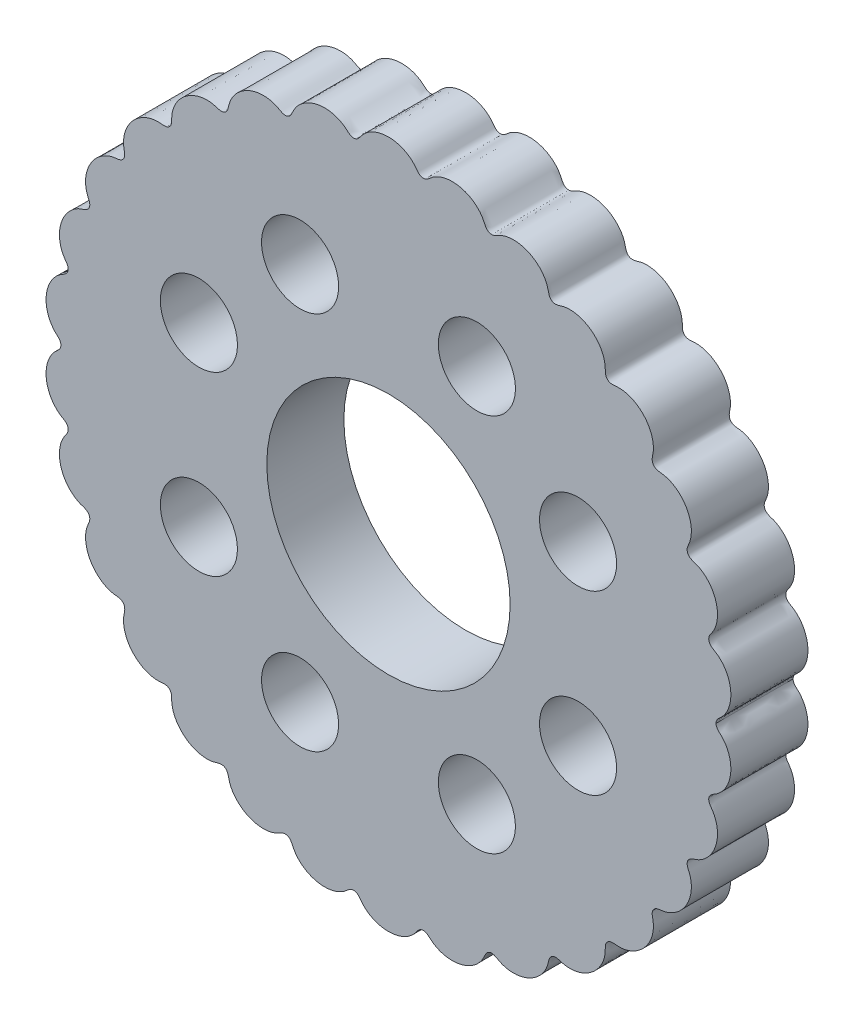
SolidWorks part; units mm, degrees
ref_plane "Plan de face" through (0, 0, 0) normal (0, 0, 1) x (1, 0, 0)
ref_plane "Plan de dessus" through (0, 0, 0) normal (0, 1, 0) x (1, 0, 0)
ref_plane "Plan de droite" through (0, 0, 0) normal (1, 0, 0) x (0, 0, -1)
sketch "Esquisse1" plane through (0, 0, 0) normal (0, 0, 1) x (1, 0, 0)
  line L0 (-1000, 0) -> (49000, 0) construction
  spline S0 degree 4 poles (29.8631, 8.2305) (29.8499, 8.1217) (29.8133, 7.9053) (29.7416, 7.64) (29.6157, 7.3353) (29.4839, 7.095) (29.3642, 6.911) (29.2467, 6.7537) (29.1538, 6.6056) (29.0902, 6.432) (29.0737, 6.2397) (29.1354, 6.023) (29.2904, 5.838) (29.4774, 5.7198) (29.6579, 5.6163) (29.8231, 5.5082) (30.0196, 5.3594) (30.2372, 5.1583) (30.5232, 4.8242) (30.8216, 4.3213) (31.0469, 3.679) (31.1337, 2.9091) (31.0567, 2.2277) (30.8902, 1.7108) (30.7109, 1.353) (30.5728, 1.1334) (30.4496, 0.9663) (30.3139, 0.8094) (30.1671, 0.6626) (30.0393, 0.549) (29.9425, 0.4546) (29.8803, 0.3777) (29.8449, 0.3262) (29.8141, 0.2716) (29.7888, 0.2141) (29.7717, 0.1632) (29.761, 0.1169) (29.7536, 0.0672) (29.7495, 0.017) (29.7494, -0.0206) (29.7556, -0.0898) (29.7678, -0.1499) (29.7904, -0.2203) (29.8284, -0.303) (29.8828, -0.3847) (29.9529, -0.4642) (30.04, -0.5488) (30.1416, -0.6407) (30.2572, -0.7512) (30.3813, -0.8854) (30.4962, -1.0277) (30.6276, -1.2147) (30.7721, -1.4641) (30.9126, -1.7829) (31.0276, -2.1744) (31.0935, -2.591) (31.107, -3.0187) (31.0662, -3.4508) (30.9693, -3.8803) (30.8145, -4.2991) (30.6117, -4.6792) (30.3965, -4.9766) (30.1917, -5.1998) (30.0146, -5.3603) (29.8643, -5.4786) (29.7061, -5.5858) (29.542, -5.684) (29.3671, -5.785) (29.2042, -5.9269) (29.0936, -6.1295) (29.0703, -6.371) (29.1391, -6.5914) (29.2598, -6.7697) (29.3791, -6.934) (29.4834, -7.0955) (29.5997, -7.3056) (29.715, -7.5703) (29.8147, -7.8969) (29.8798, -8.2857) (29.896, -8.684) (29.8631, -9.0858) (29.7829, -9.4799) (29.6574, -9.8612) (29.4885, -10.2243) (29.2783, -10.5643) (29.0303, -10.8742) (28.7824, -11.1148) (28.5506, -11.2952) (28.3468, -11.4258) (28.1768, -11.5188) (28.0006, -11.599) (27.8193, -11.6676) (27.6244, -11.7296) (27.4217, -11.8089) (27.242, -11.9571) (27.1301, -12.1734) (27.113, -12.404) (27.1707, -12.6114) (27.2542, -12.795) (27.3276, -12.9715) (27.3906, -13.1518) (27.4404, -13.3363) (27.4866, -13.5706) (27.5177, -13.8717) (27.5133, -14.2384) (27.4499, -14.6642) (27.3252, -15.0926) (27.1465, -15.4978) (26.919, -15.8739) (26.6474, -16.2153) (26.3365, -16.5168) (26.0024, -16.764) (25.654, -16.9563) (25.3418, -17.0779) (25.0791, -17.148) (24.8562, -17.1866) (24.6765, -17.2082) (24.4854, -17.2287) (24.2872, -17.2853) (24.1038, -17.4139) (23.9758, -17.6159) (23.9376, -17.8434) (23.9703, -18.0586) (24.0141, -18.2584) (24.0453, -18.4498) (24.0639, -18.6424) (24.0684, -18.8361) (24.0572, -19.0779) (24.0169, -19.3689) (23.9324, -19.7039) (23.7881, -20.0736) (23.5988, -20.4256) (23.3687, -20.7534) (23.1013, -21.0528) (22.8001, -21.3193) (22.4685, -21.5487) (22.1155, -21.7338) (21.7463, -21.8718) (21.4135, -21.9488) (21.1267, -21.9813) (20.8866, -21.9856) (20.6945, -21.9761) (20.4927, -21.9549) (20.2778, -21.9395) (20.0526, -21.9901) (19.8551, -22.131) (19.7349, -22.3281) (19.6935, -22.5401) (19.6935, -22.7421) (19.6905, -22.9333) (19.6768, -23.124) (19.6495, -23.3133) (19.599, -23.5469) (19.5081, -23.8358) (19.3582, -24.1709) (19.1304, -24.5365) (18.8451, -24.88) (18.5216, -25.1787) (18.1677, -25.4301) (17.7906, -25.6322) (17.3968, -25.7835) (17.0003, -25.8796) (16.6085, -25.9224) (16.2742, -25.9148) (16.002, -25.8785) (15.7793, -25.8278) (15.6036, -25.7769) (15.4169, -25.7147) (15.2087, -25.6689) (14.9779, -25.6954) (14.7639, -25.8189) (14.6256, -26.0056) (14.5611, -26.2088) (14.5217, -26.4015) (14.4779, -26.5791) (14.4104, -26.7974) (14.3058, -27.0513) (14.1452, -27.3445) (13.9122, -27.6625) (13.6308, -27.9579) (13.3029, -28.2232) (12.9393, -28.4488) (12.5446, -28.6295) (12.1242, -28.7604) (11.6841, -28.8357) (11.2535, -28.8501) (10.8884, -28.8124) (10.5927, -28.7466) (10.3651, -28.6736) (10.1875, -28.6026) (10.0156, -28.5191) (9.8485, -28.4261) (9.6736, -28.3252) (9.4693, -28.255) (9.2385, -28.2605) (9.0177, -28.3611) (8.8612, -28.5309) (8.7671, -28.7246) (8.6846, -28.91) (8.5968, -29.0812) (8.473, -29.2869) (8.3014, -29.519) (8.0684, -29.7687) (7.7643, -30.0195) (7.4274, -30.2327) (7.0631, -30.4051) (6.6816, -30.5327) (6.2887, -30.6146) (5.8897, -30.6499) (5.4902, -30.6379) (5.0979, -30.5781) (4.7655, -30.4837) (4.4934, -30.3731) (4.2784, -30.2619) (4.1128, -30.1612) (3.9553, -30.0487) (3.8052, -29.926) (3.6541, -29.7882) (3.484, -29.6523) (3.2679, -29.5716) (3.029, -29.5815) (2.8259, -29.676) (2.6778, -29.8193) (2.5645, -29.9746) (2.456, -30.1194) (2.311, -30.2931) (2.119, -30.4856) (1.8576, -30.6952) (1.5168, -30.9007) (1.1357, -31.0665) (0.7192, -31.185) (0.2877, -31.2495) (-0.1517, -31.2585) (-0.592, -31.2106) (-1.0254, -31.1045) (-1.4258, -30.9464) (-1.7456, -30.7669) (-1.9908, -30.5894) (-2.1706, -30.4322) (-2.3055, -30.2968) (-2.4301, -30.1521) (-2.5463, -30.0003) (-2.6635, -29.8363) (-2.8143, -29.6826) (-3.0226, -29.582) (-3.2659, -29.5708) (-3.484, -29.6523) (-3.654, -29.7882) (-3.8052, -29.926) (-3.9553, -30.0487) (-4.1128, -30.1612) (-4.2784, -30.2619) (-4.4934, -30.3731) (-4.7655, -30.4837) (-5.0979, -30.5781) (-5.4902, -30.6379) (-5.8897, -30.6499) (-6.2887, -30.6146) (-6.6816, -30.5327) (-7.0631, -30.4051) (-7.4274, -30.2327) (-7.7643, -30.0195) (-8.0684, -29.7687) (-8.3014, -29.519) (-8.473, -29.2869) (-8.5968, -29.0812) (-8.6846, -28.91) (-8.7671, -28.7246) (-8.8612, -28.5309) (-9.0177, -28.3611) (-9.2385, -28.2605) (-9.4693, -28.255) (-9.6736, -28.3252) (-9.8485, -28.4261) (-10.0156, -28.5191) (-10.1875, -28.6026) (-10.3651, -28.6736) (-10.5927, -28.7466) (-10.8884, -28.8124) (-11.2535, -28.8501) (-11.6841, -28.8357) (-12.1242, -28.7604) (-12.5446, -28.6295) (-12.9393, -28.4488) (-13.3029, -28.2232) (-13.6308, -27.9579) (-13.9122, -27.6625) (-14.1452, -27.3445) (-14.3058, -27.0513) (-14.4104, -26.7974) (-14.4779, -26.5791) (-14.5217, -26.4015) (-14.5611, -26.2088) (-14.6256, -26.0056) (-14.7639, -25.8189) (-14.9779, -25.6954) (-15.2087, -25.6689) (-15.4169, -25.7147) (-15.6036, -25.7769) (-15.7793, -25.8278) (-16.002, -25.8785) (-16.2742, -25.9148) (-16.6085, -25.9224) (-17.0003, -25.8796) (-17.3968, -25.7835) (-17.7906, -25.6322) (-18.1677, -25.4301) (-18.5216, -25.1787) (-18.8451, -24.88) (-19.1304, -24.5365) (-19.3582, -24.1709) (-19.5081, -23.8358) (-19.599, -23.5469) (-19.6495, -23.3133) (-19.6768, -23.124) (-19.6905, -22.9333) (-19.6935, -22.7421) (-19.6935, -22.5401) (-19.7349, -22.3281) (-19.8551, -22.131) (-20.0526, -21.9901) (-20.2778, -21.9395) (-20.4927, -21.9549) (-20.6945, -21.9761) (-20.8866, -21.9856) (-21.1267, -21.9813) (-21.4135, -21.9488) (-21.7463, -21.8718) (-22.1155, -21.7338) (-22.4685, -21.5487) (-22.8001, -21.3193) (-23.1013, -21.0528) (-23.3687, -20.7534) (-23.5988, -20.4256) (-23.7881, -20.0736) (-23.9324, -19.7039) (-24.0169, -19.3689) (-24.0572, -19.0779) (-24.0684, -18.8361) (-24.0639, -18.6424) (-24.0453, -18.4498) (-24.0141, -18.2584) (-23.9703, -18.0586) (-23.9376, -17.8434) (-23.9758, -17.6159) (-24.1038, -17.4139) (-24.2872, -17.2853) (-24.4854, -17.2287) (-24.6765, -17.2082) (-24.8562, -17.1866) (-25.0791, -17.148) (-25.3418, -17.0779) (-25.654, -16.9563) (-26.0024, -16.764) (-26.3365, -16.5168) (-26.6474, -16.2153) (-26.919, -15.8739) (-27.1465, -15.4978) (-27.3252, -15.0926) (-27.4499, -14.6642) (-27.5133, -14.2384) (-27.5177, -13.8717) (-27.4866, -13.5706) (-27.4404, -13.3363) (-27.3906, -13.1518) (-27.3276, -12.9715) (-27.2542, -12.795) (-27.1707, -12.6114) (-27.113, -12.404) (-27.1301, -12.1734) (-27.242, -11.9571) (-27.4217, -11.8089) (-27.6244, -11.7296) (-27.8193, -11.6676) (-28.0006, -11.599) (-28.1768, -11.5188) (-28.3468, -11.4258) (-28.5506, -11.2952) (-28.7824, -11.1148) (-29.0303, -10.8742) (-29.2783, -10.5643) (-29.4885, -10.2243) (-29.6574, -9.8612) (-29.7829, -9.4799) (-29.8631, -9.0858) (-29.896, -8.684) (-29.8798, -8.2857) (-29.8147, -7.8969) (-29.715, -7.5703) (-29.5997, -7.3056) (-29.4834, -7.0955) (-29.3791, -6.934) (-29.2598, -6.7697) (-29.1391, -6.5914) (-29.0703, -6.371) (-29.0936, -6.1295) (-29.2042, -5.9269) (-29.3671, -5.785) (-29.542, -5.684) (-29.7061, -5.5858) (-29.8643, -5.4786) (-30.0146, -5.3603) (-30.1917, -5.1998) (-30.3965, -4.9766) (-30.6117, -4.6792) (-30.8145, -4.2991) (-30.9693, -3.8803) (-31.0662, -3.4508) (-31.107, -3.0187) (-31.0935, -2.591) (-31.0276, -2.1744) (-30.9126, -1.7829) (-30.7537, -1.4222) (-30.58, -1.1364) (-30.4124, -0.919) (-30.2572, -0.7512) (-30.1416, -0.6407) (-30.04, -0.5488) (-29.9529, -0.4642) (-29.8828, -0.3847) (-29.8284, -0.303) (-29.7904, -0.2203) (-29.7678, -0.1499) (-29.7556, -0.0898) (-29.7494, -0.0206) (-29.7495, 0.0226) (-29.7561, 0.094) (-29.7693, 0.1557) (-29.7888, 0.2141) (-29.8141, 0.2716) (-29.8449, 0.3262) (-29.8803, 0.3778) (-29.9262, 0.4344) (-29.9834, 0.4947) (-30.0703, 0.5765) (-30.1854, 0.6811) (-30.3139, 0.8093) (-30.4835, 1.0056) (-30.6621, 1.2611) (-30.8291, 1.576) (-30.9678, 1.9517) (-31.0574, 2.3341) (-31.1011, 2.7166) (-31.1012, 3.1978) (-31.0148, 3.7704) (-30.8216, 4.3213) (-30.5232, 4.8242) (-30.2372, 5.1583) (-30.0196, 5.3594) (-29.8231, 5.5082) (-29.6579, 5.6163) (-29.4774, 5.7198) (-29.2904, 5.838) (-29.1354, 6.023) (-29.0737, 6.2397) (-29.0902, 6.432) (-29.1538, 6.6056) (-29.2467, 6.7537) (-29.3642, 6.911) (-29.4839, 7.095) (-29.6157, 7.3353) (-29.7416, 7.64) (-29.8133, 7.9053) (-29.8499, 8.1217) (-29.8631, 8.2305) knots 0 0 0 0 0 0.003392 0.006784 0.00848 0.010176 0.011872 0.013568 0.014566 0.015563 0.017559 0.01944 0.02132 0.022846 0.024371 0.025896 0.027421 0.030471 0.033522 0.039468 0.045414 0.051361 0.057307 0.060517 0.062121 0.063726 0.065331 0.066935 0.06854 0.070145 0.070628 0.071112 0.071596 0.07208 0.072564 0.073048 0.073289 0.073531 0.074015 0.07448 0.074945 0.07541 0.075875 0.076805 0.077735 0.078442 0.079149 0.080563 0.081977 0.083391 0.084805 0.086218 0.089046 0.092302 0.095557 0.098813 0.102069 0.105514 0.10896 0.112405 0.115851 0.118808 0.120287 0.121766 0.123244 0.124723 0.126202 0.12768 0.1295 0.131319 0.133154 0.134989 0.136475 0.137961 0.139448 0.140934 0.143906 0.146878 0.14999 0.153103 0.156215 0.159327 0.162414 0.1655 0.168586 0.171672 0.174668 0.176165 0.177663 0.179161 0.180659 0.182156 0.183654 0.185506 0.187357 0.189175 0.190994 0.192471 0.193949 0.195426 0.196904 0.198382 0.199859 0.202814 0.206257 0.2097 0.213143 0.216586 0.219928 0.22327 0.226613 0.229955 0.232755 0.235555 0.236955 0.238355 0.239755 0.241155 0.242909 0.244663 0.246515 0.248366 0.249864 0.251362 0.252859 0.254357 0.255855 0.257353 0.260348 0.263434 0.266521 0.269607 0.272693 0.275805 0.278918 0.28203 0.285143 0.288115 0.291087 0.292573 0.294059 0.295545 0.297031 0.298866 0.300701 0.302521 0.30434 0.305819 0.307297 0.308776 0.310255 0.311733 0.313212 0.31617 0.319615 0.323061 0.326506 0.329952 0.333207 0.336463 0.339719 0.342974 0.345802 0.34863 0.350043 0.351457 0.352871 0.354285 0.356145 0.358005 0.359865 0.361725 0.363139 0.364553 0.365967 0.367381 0.370208 0.373036 0.376292 0.379547 0.382803 0.386059 0.389504 0.39295 0.396395 0.399841 0.402798 0.404277 0.405755 0.407234 0.408713 0.410191 0.41167 0.41349 0.415309 0.417144 0.418979 0.420465 0.421951 0.423437 0.424923 0.427896 0.430868 0.43398 0.437092 0.440205 0.443317 0.446403 0.44949 0.452576 0.455662 0.458657 0.460155 0.461653 0.463151 0.464649 0.466146 0.467644 0.469495 0.471347 0.473101 0.474856 0.476256 0.477656 0.479056 0.480456 0.483256 0.486055 0.489398 0.49274 0.496082 0.499424 0.502867 0.50631 0.509753 0.513196 0.516151 0.517629 0.519106 0.520584 0.522061 0.523539 0.525016 0.526835 0.528653 0.530505 0.532356 0.533854 0.535351 0.536849 0.538347 0.539845 0.541343 0.544338 0.547424 0.55051 0.553597 0.556683 0.559795 0.562908 0.56602 0.569132 0.572104 0.575077 0.576563 0.578049 0.579535 0.581021 0.582856 0.584691 0.58651 0.58833 0.589809 0.591287 0.592766 0.594245 0.595723 0.597202 0.600159 0.603605 0.60705 0.610496 0.613941 0.617197 0.620453 0.623708 0.626964 0.629792 0.632619 0.634033 0.635447 0.636861 0.638275 0.640135 0.641995 0.643855 0.645715 0.647129 0.648543 0.649957 0.65137 0.654198 0.657026 0.660281 0.663537 0.666793 0.670048 0.673494 0.676939 0.680385 0.68383 0.686788 0.688267 0.689745 0.691224 0.692703 0.694181 0.69566 0.697479 0.699299 0.701134 0.702969 0.704455 0.705941 0.707427 0.708913 0.711885 0.714857 0.71797 0.721082 0.724195 0.727307 0.730393 0.733479 0.736566 0.739652 0.742647 0.744145 0.745643 0.747141 0.748638 0.750136 0.751634 0.753485 0.755337 0.757091 0.758845 0.760245 0.761645 0.763045 0.764445 0.767245 0.770045 0.773387 0.77673 0.780072 0.783414 0.786857 0.7903 0.793743 0.797186 0.800141 0.801618 0.803096 0.804574 0.806051 0.807529 0.809006 0.810825 0.812643 0.814494 0.816346 0.817844 0.819341 0.820839 0.822337 0.823835 0.825332 0.828328 0.831414 0.8345 0.837586 0.840673 0.843785 0.846897 0.85001 0.853122 0.856094 0.859066 0.860552 0.862039 0.863525 0.865011 0.866846 0.868681 0.8705 0.87232 0.873798 0.875277 0.876756 0.878234 0.879713 0.881192 0.884149 0.887595 0.89104 0.894486 0.897931 0.901187 0.904443 0.907698 0.910954 0.913782 0.916609 0.918023 0.919437 0.920851 0.921558 0.922265 0.923195 0.924125 0.92459 0.925055 0.92552 0.925985 0.926469 0.926952 0.927436 0.92792 0.928404 0.928888 0.929372 0.929855 0.930658 0.93146 0.933065 0.934669 0.936274 0.939483 0.942693 0.945666 0.948639 0.951612 0.954586 0.960532 0.966478 0.969529 0.972579 0.974104 0.975629 0.977154 0.97868 0.98056 0.982441 0.984437 0.985434 0.986432 0.988128 0.989824 0.99152 0.993216 0.996608 1 1 1 1 1 construction
  spline S1 degree 4 poles (29.75, 0) (29.75, -0.0128) (29.751, -0.0384) (29.7556, -0.0898) (29.7678, -0.1499) (29.7904, -0.2203) (29.8284, -0.303) (29.8828, -0.3847) (29.9529, -0.4642) (30.04, -0.5488) (30.1416, -0.6407) (30.2572, -0.7512) (30.3813, -0.8854) (30.4962, -1.0277) (30.6276, -1.2147) (30.7721, -1.4641) (30.9126, -1.7829) (31.0276, -2.1744) (31.0935, -2.591) (31.107, -3.0187) (31.0662, -3.4508) (30.9693, -3.8803) (30.8145, -4.2991) (30.6117, -4.6792) (30.3965, -4.9766) (30.1917, -5.1998) (30.0146, -5.3603) (29.8643, -5.4786) (29.7061, -5.5858) (29.542, -5.684) (29.3671, -5.785) (29.2042, -5.9269) (29.0936, -6.1295) (29.0703, -6.371) (29.1391, -6.5914) (29.2598, -6.7697) (29.3791, -6.934) (29.4834, -7.0955) (29.5997, -7.3056) (29.715, -7.5703) (29.8147, -7.8969) (29.8798, -8.2857) (29.896, -8.684) (29.8631, -9.0858) (29.7829, -9.4799) (29.6574, -9.8612) (29.4885, -10.2243) (29.2783, -10.5643) (29.0303, -10.8742) (28.7824, -11.1148) (28.5506, -11.2952) (28.3468, -11.4258) (28.1768, -11.5188) (28.0006, -11.599) (27.8193, -11.6676) (27.6244, -11.7296) (27.4217, -11.8089) (27.242, -11.9571) (27.1301, -12.1734) (27.113, -12.404) (27.1707, -12.6114) (27.2542, -12.795) (27.3276, -12.9715) (27.3906, -13.1518) (27.4404, -13.3363) (27.4866, -13.5706) (27.5177, -13.8717) (27.5133, -14.2384) (27.4499, -14.6642) (27.3252, -15.0926) (27.1465, -15.4978) (26.919, -15.8739) (26.6474, -16.2153) (26.3365, -16.5168) (26.0024, -16.764) (25.654, -16.9563) (25.3418, -17.0779) (25.0791, -17.148) (24.8562, -17.1866) (24.6765, -17.2082) (24.4854, -17.2287) (24.2872, -17.2853) (24.1038, -17.4139) (23.9758, -17.6159) (23.9376, -17.8434) (23.9703, -18.0586) (24.0141, -18.2584) (24.0453, -18.4498) (24.0639, -18.6424) (24.0684, -18.8361) (24.0572, -19.0779) (24.0169, -19.3689) (23.9324, -19.7039) (23.7881, -20.0736) (23.5988, -20.4256) (23.3687, -20.7534) (23.1013, -21.0528) (22.8001, -21.3193) (22.4685, -21.5487) (22.1155, -21.7338) (21.7463, -21.8718) (21.4135, -21.9488) (21.1267, -21.9813) (20.8866, -21.9856) (20.6945, -21.9761) (20.4927, -21.9549) (20.2778, -21.9395) (20.0526, -21.9901) (19.8551, -22.131) (19.7349, -22.3281) (19.6935, -22.5401) (19.6935, -22.7421) (19.6905, -22.9333) (19.6768, -23.124) (19.6495, -23.3133) (19.599, -23.5469) (19.5081, -23.8358) (19.3582, -24.1709) (19.1304, -24.5365) (18.8451, -24.88) (18.5216, -25.1787) (18.1677, -25.4301) (17.7906, -25.6322) (17.3968, -25.7835) (17.0003, -25.8796) (16.6085, -25.9224) (16.2742, -25.9148) (16.002, -25.8785) (15.7793, -25.8278) (15.6036, -25.7769) (15.4169, -25.7147) (15.2087, -25.6689) (14.9779, -25.6954) (14.7639, -25.8189) (14.6256, -26.0056) (14.5611, -26.2088) (14.5217, -26.4015) (14.4779, -26.5791) (14.4104, -26.7974) (14.3058, -27.0513) (14.1452, -27.3445) (13.9122, -27.6625) (13.6308, -27.9579) (13.3029, -28.2232) (12.9393, -28.4488) (12.5446, -28.6295) (12.1242, -28.7604) (11.6841, -28.8357) (11.2535, -28.8501) (10.8884, -28.8124) (10.5927, -28.7466) (10.3651, -28.6736) (10.1875, -28.6026) (10.0156, -28.5191) (9.8485, -28.4261) (9.6736, -28.3252) (9.4693, -28.255) (9.2385, -28.2605) (9.0177, -28.3611) (8.8612, -28.5309) (8.7671, -28.7246) (8.6846, -28.91) (8.5968, -29.0812) (8.473, -29.2869) (8.3014, -29.519) (8.0684, -29.7687) (7.7643, -30.0195) (7.4274, -30.2327) (7.0631, -30.4051) (6.6816, -30.5327) (6.2887, -30.6146) (5.8897, -30.6499) (5.4902, -30.6379) (5.0979, -30.5781) (4.7655, -30.4837) (4.4934, -30.3731) (4.2784, -30.2619) (4.1128, -30.1612) (3.9553, -30.0487) (3.8052, -29.926) (3.6541, -29.7882) (3.484, -29.6523) (3.2679, -29.5716) (3.029, -29.5815) (2.8259, -29.676) (2.6778, -29.8193) (2.5645, -29.9746) (2.456, -30.1194) (2.311, -30.2931) (2.119, -30.4856) (1.8576, -30.6952) (1.5168, -30.9007) (1.1357, -31.0665) (0.7192, -31.185) (0.2877, -31.2495) (-0.1517, -31.2585) (-0.592, -31.2106) (-1.0254, -31.1045) (-1.4258, -30.9464) (-1.7456, -30.7669) (-1.9908, -30.5894) (-2.1706, -30.4322) (-2.3055, -30.2968) (-2.4301, -30.1521) (-2.5463, -30.0003) (-2.6635, -29.8363) (-2.8143, -29.6826) (-3.0226, -29.582) (-3.2659, -29.5708) (-3.484, -29.6523) (-3.654, -29.7882) (-3.8052, -29.926) (-3.9553, -30.0487) (-4.1128, -30.1612) (-4.2784, -30.2619) (-4.4934, -30.3731) (-4.7655, -30.4837) (-5.0979, -30.5781) (-5.4902, -30.6379) (-5.8897, -30.6499) (-6.2887, -30.6146) (-6.6816, -30.5327) (-7.0631, -30.4051) (-7.4274, -30.2327) (-7.7643, -30.0195) (-8.0684, -29.7687) (-8.3014, -29.519) (-8.473, -29.2869) (-8.5968, -29.0812) (-8.6846, -28.91) (-8.7671, -28.7246) (-8.8612, -28.5309) (-9.0177, -28.3611) (-9.2385, -28.2605) (-9.4693, -28.255) (-9.6736, -28.3252) (-9.8485, -28.4261) (-10.0156, -28.5191) (-10.1875, -28.6026) (-10.3651, -28.6736) (-10.5927, -28.7466) (-10.8884, -28.8124) (-11.2535, -28.8501) (-11.6841, -28.8357) (-12.1242, -28.7604) (-12.5446, -28.6295) (-12.9393, -28.4488) (-13.3029, -28.2232) (-13.6308, -27.9579) (-13.9122, -27.6625) (-14.1452, -27.3445) (-14.3058, -27.0513) (-14.4104, -26.7974) (-14.4779, -26.5791) (-14.5217, -26.4015) (-14.5611, -26.2088) (-14.6256, -26.0056) (-14.7639, -25.8189) (-14.9779, -25.6954) (-15.2087, -25.6689) (-15.4169, -25.7147) (-15.6036, -25.7769) (-15.7793, -25.8278) (-16.002, -25.8785) (-16.2742, -25.9148) (-16.6085, -25.9224) (-17.0003, -25.8796) (-17.3968, -25.7835) (-17.7906, -25.6322) (-18.1677, -25.4301) (-18.5216, -25.1787) (-18.8451, -24.88) (-19.1304, -24.5365) (-19.3582, -24.1709) (-19.5081, -23.8358) (-19.599, -23.5469) (-19.6495, -23.3133) (-19.6768, -23.124) (-19.6905, -22.9333) (-19.6935, -22.7421) (-19.6935, -22.5401) (-19.7349, -22.3281) (-19.8551, -22.131) (-20.0526, -21.9901) (-20.2778, -21.9395) (-20.4927, -21.9549) (-20.6945, -21.9761) (-20.8866, -21.9856) (-21.1267, -21.9813) (-21.4135, -21.9488) (-21.7463, -21.8718) (-22.1155, -21.7338) (-22.4685, -21.5487) (-22.8001, -21.3193) (-23.1013, -21.0528) (-23.3687, -20.7534) (-23.5988, -20.4256) (-23.7881, -20.0736) (-23.9324, -19.7039) (-24.0169, -19.3689) (-24.0572, -19.0779) (-24.0684, -18.8361) (-24.0639, -18.6424) (-24.0453, -18.4498) (-24.0141, -18.2584) (-23.9703, -18.0586) (-23.9376, -17.8434) (-23.9758, -17.6159) (-24.1038, -17.4139) (-24.2872, -17.2853) (-24.4854, -17.2287) (-24.6765, -17.2082) (-24.8562, -17.1866) (-25.0791, -17.148) (-25.3418, -17.0779) (-25.654, -16.9563) (-26.0024, -16.764) (-26.3365, -16.5168) (-26.6474, -16.2153) (-26.919, -15.8739) (-27.1465, -15.4978) (-27.3252, -15.0926) (-27.4499, -14.6642) (-27.5133, -14.2384) (-27.5177, -13.8717) (-27.4866, -13.5706) (-27.4404, -13.3363) (-27.3906, -13.1518) (-27.3276, -12.9715) (-27.2542, -12.795) (-27.1707, -12.6114) (-27.113, -12.404) (-27.1301, -12.1734) (-27.242, -11.9571) (-27.4217, -11.8089) (-27.6244, -11.7296) (-27.8193, -11.6676) (-28.0006, -11.599) (-28.1768, -11.5188) (-28.3468, -11.4258) (-28.5506, -11.2952) (-28.7824, -11.1148) (-29.0303, -10.8742) (-29.2783, -10.5643) (-29.4885, -10.2243) (-29.6574, -9.8612) (-29.7829, -9.4799) (-29.8631, -9.0858) (-29.896, -8.684) (-29.8798, -8.2857) (-29.8147, -7.8969) (-29.715, -7.5703) (-29.5997, -7.3056) (-29.4834, -7.0955) (-29.3791, -6.934) (-29.2598, -6.7697) (-29.1391, -6.5914) (-29.0703, -6.371) (-29.0936, -6.1295) (-29.2042, -5.9269) (-29.3671, -5.785) (-29.542, -5.684) (-29.7061, -5.5858) (-29.8643, -5.4786) (-30.0146, -5.3603) (-30.1917, -5.1998) (-30.3965, -4.9766) (-30.6117, -4.6792) (-30.8145, -4.2991) (-30.9693, -3.8803) (-31.0662, -3.4508) (-31.107, -3.0187) (-31.0935, -2.591) (-31.0276, -2.1744) (-30.9126, -1.7829) (-30.7537, -1.4222) (-30.58, -1.1364) (-30.4124, -0.919) (-30.2572, -0.7512) (-30.1416, -0.6407) (-30.04, -0.5488) (-29.9529, -0.4642) (-29.8828, -0.3847) (-29.8284, -0.303) (-29.7904, -0.2203) (-29.7678, -0.1499) (-29.7556, -0.0898) (-29.751, -0.0384) (-29.75, -0.0128) (-29.75, 0) knots 0.074015 0.074015 0.074015 0.074015 0.074015 0.07448 0.074945 0.07541 0.075875 0.076805 0.077735 0.078442 0.079149 0.080563 0.081977 0.083391 0.084805 0.086218 0.089046 0.092302 0.095557 0.098813 0.102069 0.105514 0.10896 0.112405 0.115851 0.118808 0.120287 0.121766 0.123244 0.124723 0.126202 0.12768 0.1295 0.131319 0.133154 0.134989 0.136475 0.137961 0.139448 0.140934 0.143906 0.146878 0.14999 0.153103 0.156215 0.159327 0.162414 0.1655 0.168586 0.171672 0.174668 0.176165 0.177663 0.179161 0.180659 0.182156 0.183654 0.185506 0.187357 0.189175 0.190994 0.192471 0.193949 0.195426 0.196904 0.198382 0.199859 0.202814 0.206257 0.2097 0.213143 0.216586 0.219928 0.22327 0.226613 0.229955 0.232755 0.235555 0.236955 0.238355 0.239755 0.241155 0.242909 0.244663 0.246515 0.248366 0.249864 0.251362 0.252859 0.254357 0.255855 0.257353 0.260348 0.263434 0.266521 0.269607 0.272693 0.275805 0.278918 0.28203 0.285143 0.288115 0.291087 0.292573 0.294059 0.295545 0.297031 0.298866 0.300701 0.302521 0.30434 0.305819 0.307297 0.308776 0.310255 0.311733 0.313212 0.31617 0.319615 0.323061 0.326506 0.329952 0.333207 0.336463 0.339719 0.342974 0.345802 0.34863 0.350043 0.351457 0.352871 0.354285 0.356145 0.358005 0.359865 0.361725 0.363139 0.364553 0.365967 0.367381 0.370208 0.373036 0.376292 0.379547 0.382803 0.386059 0.389504 0.39295 0.396395 0.399841 0.402798 0.404277 0.405755 0.407234 0.408713 0.410191 0.41167 0.41349 0.415309 0.417144 0.418979 0.420465 0.421951 0.423437 0.424923 0.427896 0.430868 0.43398 0.437092 0.440205 0.443317 0.446403 0.44949 0.452576 0.455662 0.458657 0.460155 0.461653 0.463151 0.464649 0.466146 0.467644 0.469495 0.471347 0.473101 0.474856 0.476256 0.477656 0.479056 0.480456 0.483256 0.486055 0.489398 0.49274 0.496082 0.499424 0.502867 0.50631 0.509753 0.513196 0.516151 0.517629 0.519106 0.520584 0.522061 0.523539 0.525016 0.526835 0.528653 0.530505 0.532356 0.533854 0.535351 0.536849 0.538347 0.539845 0.541343 0.544338 0.547424 0.55051 0.553597 0.556683 0.559795 0.562908 0.56602 0.569132 0.572104 0.575077 0.576563 0.578049 0.579535 0.581021 0.582856 0.584691 0.58651 0.58833 0.589809 0.591287 0.592766 0.594245 0.595723 0.597202 0.600159 0.603605 0.60705 0.610496 0.613941 0.617197 0.620453 0.623708 0.626964 0.629792 0.632619 0.634033 0.635447 0.636861 0.638275 0.640135 0.641995 0.643855 0.645715 0.647129 0.648543 0.649957 0.65137 0.654198 0.657026 0.660281 0.663537 0.666793 0.670048 0.673494 0.676939 0.680385 0.68383 0.686788 0.688267 0.689745 0.691224 0.692703 0.694181 0.69566 0.697479 0.699299 0.701134 0.702969 0.704455 0.705941 0.707427 0.708913 0.711885 0.714857 0.71797 0.721082 0.724195 0.727307 0.730393 0.733479 0.736566 0.739652 0.742647 0.744145 0.745643 0.747141 0.748638 0.750136 0.751634 0.753485 0.755337 0.757091 0.758845 0.760245 0.761645 0.763045 0.764445 0.767245 0.770045 0.773387 0.77673 0.780072 0.783414 0.786857 0.7903 0.793743 0.797186 0.800141 0.801618 0.803096 0.804574 0.806051 0.807529 0.809006 0.810825 0.812643 0.814494 0.816346 0.817844 0.819341 0.820839 0.822337 0.823835 0.825332 0.828328 0.831414 0.8345 0.837586 0.840673 0.843785 0.846897 0.85001 0.853122 0.856094 0.859066 0.860552 0.862039 0.863525 0.865011 0.866846 0.868681 0.8705 0.87232 0.873798 0.875277 0.876756 0.878234 0.879713 0.881192 0.884149 0.887595 0.89104 0.894486 0.897931 0.901187 0.904443 0.907698 0.910954 0.913782 0.916609 0.918023 0.919437 0.920851 0.921558 0.922265 0.923195 0.924125 0.92459 0.925055 0.92552 0.925985 0.925985 0.925985 0.925985 0.925985 construction
  spline S2 degree 4 poles (29.75, 0) (29.75, 0.0128) (29.751, 0.0384) (29.7556, 0.0898) (29.7678, 0.1499) (29.7904, 0.2203) (29.8284, 0.303) (29.8828, 0.3847) (29.9529, 0.4642) (30.04, 0.5488) (30.1416, 0.6407) (30.2572, 0.7512) (30.3813, 0.8854) (30.4962, 1.0277) (30.6276, 1.2147) (30.7721, 1.4641) (30.9126, 1.7829) (31.0276, 2.1744) (31.0935, 2.591) (31.107, 3.0187) (31.0662, 3.4508) (30.9693, 3.8803) (30.8145, 4.2991) (30.6117, 4.6792) (30.3965, 4.9766) (30.1917, 5.1998) (30.0146, 5.3603) (29.8643, 5.4786) (29.7061, 5.5858) (29.542, 5.684) (29.3671, 5.785) (29.2042, 5.9269) (29.0936, 6.1295) (29.0703, 6.371) (29.1391, 6.5914) (29.2598, 6.7697) (29.3791, 6.934) (29.4834, 7.0955) (29.5997, 7.3056) (29.715, 7.5703) (29.8147, 7.8969) (29.8798, 8.2857) (29.896, 8.684) (29.8631, 9.0858) (29.7829, 9.4799) (29.6574, 9.8612) (29.4885, 10.2243) (29.2783, 10.5643) (29.0303, 10.8742) (28.7824, 11.1148) (28.5506, 11.2952) (28.3468, 11.4258) (28.1768, 11.5188) (28.0006, 11.599) (27.8193, 11.6676) (27.6244, 11.7296) (27.4217, 11.8089) (27.242, 11.9571) (27.1301, 12.1734) (27.113, 12.404) (27.1707, 12.6114) (27.2542, 12.795) (27.3276, 12.9715) (27.3906, 13.1518) (27.4404, 13.3363) (27.4866, 13.5706) (27.5177, 13.8717) (27.5133, 14.2384) (27.4499, 14.6642) (27.3252, 15.0926) (27.1465, 15.4978) (26.919, 15.8739) (26.6474, 16.2153) (26.3365, 16.5168) (26.0024, 16.764) (25.654, 16.9563) (25.3418, 17.0779) (25.0791, 17.148) (24.8562, 17.1866) (24.6765, 17.2082) (24.4854, 17.2287) (24.2872, 17.2853) (24.1038, 17.4139) (23.9758, 17.6159) (23.9376, 17.8434) (23.9703, 18.0586) (24.0141, 18.2584) (24.0453, 18.4498) (24.0639, 18.6424) (24.0684, 18.8361) (24.0572, 19.0779) (24.0169, 19.3689) (23.9324, 19.7039) (23.7881, 20.0736) (23.5988, 20.4256) (23.3687, 20.7534) (23.1013, 21.0528) (22.8001, 21.3193) (22.4685, 21.5487) (22.1155, 21.7338) (21.7463, 21.8718) (21.4135, 21.9488) (21.1267, 21.9813) (20.8866, 21.9856) (20.6945, 21.9761) (20.4927, 21.9549) (20.2778, 21.9395) (20.0526, 21.9901) (19.8551, 22.131) (19.7349, 22.3281) (19.6935, 22.5401) (19.6935, 22.7421) (19.6905, 22.9333) (19.6768, 23.124) (19.6495, 23.3133) (19.599, 23.5469) (19.5081, 23.8358) (19.3582, 24.1709) (19.1304, 24.5365) (18.8451, 24.88) (18.5216, 25.1787) (18.1677, 25.4301) (17.7906, 25.6322) (17.3968, 25.7835) (17.0003, 25.8796) (16.6085, 25.9224) (16.2742, 25.9148) (16.002, 25.8785) (15.7793, 25.8278) (15.6036, 25.7769) (15.4169, 25.7147) (15.2087, 25.6689) (14.9779, 25.6954) (14.7639, 25.8189) (14.6256, 26.0056) (14.5611, 26.2088) (14.5217, 26.4015) (14.4779, 26.5791) (14.4104, 26.7974) (14.3058, 27.0513) (14.1452, 27.3445) (13.9122, 27.6625) (13.6308, 27.9579) (13.3029, 28.2232) (12.9393, 28.4488) (12.5446, 28.6295) (12.1242, 28.7604) (11.6841, 28.8357) (11.2535, 28.8501) (10.8884, 28.8124) (10.5927, 28.7466) (10.3651, 28.6736) (10.1875, 28.6026) (10.0156, 28.5191) (9.8485, 28.4261) (9.6736, 28.3252) (9.4693, 28.255) (9.2385, 28.2605) (9.0177, 28.3611) (8.8612, 28.5309) (8.7671, 28.7246) (8.6846, 28.91) (8.5968, 29.0812) (8.473, 29.2869) (8.3014, 29.519) (8.0684, 29.7687) (7.7643, 30.0195) (7.4274, 30.2327) (7.0631, 30.4051) (6.6816, 30.5327) (6.2887, 30.6146) (5.8897, 30.6499) (5.4902, 30.6379) (5.0979, 30.5781) (4.7655, 30.4837) (4.4934, 30.3731) (4.2784, 30.2619) (4.1128, 30.1612) (3.9553, 30.0487) (3.8052, 29.926) (3.6541, 29.7882) (3.484, 29.6523) (3.2679, 29.5716) (3.029, 29.5815) (2.8259, 29.676) (2.6778, 29.8193) (2.5645, 29.9746) (2.456, 30.1194) (2.311, 30.2931) (2.119, 30.4856) (1.8576, 30.6952) (1.5168, 30.9007) (1.1357, 31.0665) (0.7192, 31.185) (0.2877, 31.2495) (-0.1517, 31.2585) (-0.592, 31.2106) (-1.0254, 31.1045) (-1.4258, 30.9464) (-1.7456, 30.7669) (-1.9908, 30.5894) (-2.1706, 30.4322) (-2.3055, 30.2968) (-2.4301, 30.1521) (-2.5463, 30.0003) (-2.6635, 29.8363) (-2.8143, 29.6826) (-3.0226, 29.582) (-3.2659, 29.5708) (-3.484, 29.6523) (-3.654, 29.7882) (-3.8052, 29.926) (-3.9553, 30.0487) (-4.1128, 30.1612) (-4.2784, 30.2619) (-4.4934, 30.3731) (-4.7655, 30.4837) (-5.0979, 30.5781) (-5.4902, 30.6379) (-5.8897, 30.6499) (-6.2887, 30.6146) (-6.6816, 30.5327) (-7.0631, 30.4051) (-7.4274, 30.2327) (-7.7643, 30.0195) (-8.0684, 29.7687) (-8.3014, 29.519) (-8.473, 29.2869) (-8.5968, 29.0812) (-8.6846, 28.91) (-8.7671, 28.7246) (-8.8612, 28.5309) (-9.0177, 28.3611) (-9.2385, 28.2605) (-9.4693, 28.255) (-9.6736, 28.3252) (-9.8485, 28.4261) (-10.0156, 28.5191) (-10.1875, 28.6026) (-10.3651, 28.6736) (-10.5927, 28.7466) (-10.8884, 28.8124) (-11.2535, 28.8501) (-11.6841, 28.8357) (-12.1242, 28.7604) (-12.5446, 28.6295) (-12.9393, 28.4488) (-13.3029, 28.2232) (-13.6308, 27.9579) (-13.9122, 27.6625) (-14.1452, 27.3445) (-14.3058, 27.0513) (-14.4104, 26.7974) (-14.4779, 26.5791) (-14.5217, 26.4015) (-14.5611, 26.2088) (-14.6256, 26.0056) (-14.7639, 25.8189) (-14.9779, 25.6954) (-15.2087, 25.6689) (-15.4169, 25.7147) (-15.6036, 25.7769) (-15.7793, 25.8278) (-16.002, 25.8785) (-16.2742, 25.9148) (-16.6085, 25.9224) (-17.0003, 25.8796) (-17.3968, 25.7835) (-17.7906, 25.6322) (-18.1677, 25.4301) (-18.5216, 25.1787) (-18.8451, 24.88) (-19.1304, 24.5365) (-19.3582, 24.1709) (-19.5081, 23.8358) (-19.599, 23.5469) (-19.6495, 23.3133) (-19.6768, 23.124) (-19.6905, 22.9333) (-19.6935, 22.7421) (-19.6935, 22.5401) (-19.7349, 22.3281) (-19.8551, 22.131) (-20.0526, 21.9901) (-20.2778, 21.9395) (-20.4927, 21.9549) (-20.6945, 21.9761) (-20.8866, 21.9856) (-21.1267, 21.9813) (-21.4135, 21.9488) (-21.7463, 21.8718) (-22.1155, 21.7338) (-22.4685, 21.5487) (-22.8001, 21.3193) (-23.1013, 21.0528) (-23.3687, 20.7534) (-23.5988, 20.4256) (-23.7881, 20.0736) (-23.9324, 19.7039) (-24.0169, 19.3689) (-24.0572, 19.0779) (-24.0684, 18.8361) (-24.0639, 18.6424) (-24.0453, 18.4498) (-24.0141, 18.2584) (-23.9703, 18.0586) (-23.9376, 17.8434) (-23.9758, 17.6159) (-24.1038, 17.4139) (-24.2872, 17.2853) (-24.4854, 17.2287) (-24.6765, 17.2082) (-24.8562, 17.1866) (-25.0791, 17.148) (-25.3418, 17.0779) (-25.654, 16.9563) (-26.0024, 16.764) (-26.3365, 16.5168) (-26.6474, 16.2153) (-26.919, 15.8739) (-27.1465, 15.4978) (-27.3252, 15.0926) (-27.4499, 14.6642) (-27.5133, 14.2384) (-27.5177, 13.8717) (-27.4866, 13.5706) (-27.4404, 13.3363) (-27.3906, 13.1518) (-27.3276, 12.9715) (-27.2542, 12.795) (-27.1707, 12.6114) (-27.113, 12.404) (-27.1301, 12.1734) (-27.242, 11.9571) (-27.4217, 11.8089) (-27.6244, 11.7296) (-27.8193, 11.6676) (-28.0006, 11.599) (-28.1768, 11.5188) (-28.3468, 11.4258) (-28.5506, 11.2952) (-28.7824, 11.1148) (-29.0303, 10.8742) (-29.2783, 10.5643) (-29.4885, 10.2243) (-29.6574, 9.8612) (-29.7829, 9.4799) (-29.8631, 9.0858) (-29.896, 8.684) (-29.8798, 8.2857) (-29.8147, 7.8969) (-29.715, 7.5703) (-29.5997, 7.3056) (-29.4834, 7.0955) (-29.3791, 6.934) (-29.2598, 6.7697) (-29.1391, 6.5914) (-29.0703, 6.371) (-29.0936, 6.1295) (-29.2042, 5.9269) (-29.3671, 5.785) (-29.542, 5.684) (-29.7061, 5.5858) (-29.8643, 5.4786) (-30.0146, 5.3603) (-30.1917, 5.1998) (-30.3965, 4.9766) (-30.6117, 4.6792) (-30.8145, 4.2991) (-30.9693, 3.8803) (-31.0662, 3.4508) (-31.107, 3.0187) (-31.0935, 2.591) (-31.0276, 2.1744) (-30.9126, 1.7829) (-30.7537, 1.4222) (-30.58, 1.1364) (-30.4124, 0.919) (-30.2572, 0.7512) (-30.1416, 0.6407) (-30.04, 0.5488) (-29.9529, 0.4642) (-29.8828, 0.3847) (-29.8284, 0.303) (-29.7904, 0.2203) (-29.7678, 0.1499) (-29.7556, 0.0898) (-29.751, 0.0384) (-29.75, 0.0128) (-29.75, 0) knots 0.074015 0.074015 0.074015 0.074015 0.074015 0.07448 0.074945 0.07541 0.075875 0.076805 0.077735 0.078442 0.079149 0.080563 0.081977 0.083391 0.084805 0.086218 0.089046 0.092302 0.095557 0.098813 0.102069 0.105514 0.10896 0.112405 0.115851 0.118808 0.120287 0.121766 0.123244 0.124723 0.126202 0.12768 0.1295 0.131319 0.133154 0.134989 0.136475 0.137961 0.139448 0.140934 0.143906 0.146878 0.14999 0.153103 0.156215 0.159327 0.162414 0.1655 0.168586 0.171672 0.174668 0.176165 0.177663 0.179161 0.180659 0.182156 0.183654 0.185506 0.187357 0.189175 0.190994 0.192471 0.193949 0.195426 0.196904 0.198382 0.199859 0.202814 0.206257 0.2097 0.213143 0.216586 0.219928 0.22327 0.226613 0.229955 0.232755 0.235555 0.236955 0.238355 0.239755 0.241155 0.242909 0.244663 0.246515 0.248366 0.249864 0.251362 0.252859 0.254357 0.255855 0.257353 0.260348 0.263434 0.266521 0.269607 0.272693 0.275805 0.278918 0.28203 0.285143 0.288115 0.291087 0.292573 0.294059 0.295545 0.297031 0.298866 0.300701 0.302521 0.30434 0.305819 0.307297 0.308776 0.310255 0.311733 0.313212 0.31617 0.319615 0.323061 0.326506 0.329952 0.333207 0.336463 0.339719 0.342974 0.345802 0.34863 0.350043 0.351457 0.352871 0.354285 0.356145 0.358005 0.359865 0.361725 0.363139 0.364553 0.365967 0.367381 0.370208 0.373036 0.376292 0.379547 0.382803 0.386059 0.389504 0.39295 0.396395 0.399841 0.402798 0.404277 0.405755 0.407234 0.408713 0.410191 0.41167 0.41349 0.415309 0.417144 0.418979 0.420465 0.421951 0.423437 0.424923 0.427896 0.430868 0.43398 0.437092 0.440205 0.443317 0.446403 0.44949 0.452576 0.455662 0.458657 0.460155 0.461653 0.463151 0.464649 0.466146 0.467644 0.469495 0.471347 0.473101 0.474856 0.476256 0.477656 0.479056 0.480456 0.483256 0.486055 0.489398 0.49274 0.496082 0.499424 0.502867 0.50631 0.509753 0.513196 0.516151 0.517629 0.519106 0.520584 0.522061 0.523539 0.525016 0.526835 0.528653 0.530505 0.532356 0.533854 0.535351 0.536849 0.538347 0.539845 0.541343 0.544338 0.547424 0.55051 0.553597 0.556683 0.559795 0.562908 0.56602 0.569132 0.572104 0.575077 0.576563 0.578049 0.579535 0.581021 0.582856 0.584691 0.58651 0.58833 0.589809 0.591287 0.592766 0.594245 0.595723 0.597202 0.600159 0.603605 0.60705 0.610496 0.613941 0.617197 0.620453 0.623708 0.626964 0.629792 0.632619 0.634033 0.635447 0.636861 0.638275 0.640135 0.641995 0.643855 0.645715 0.647129 0.648543 0.649957 0.65137 0.654198 0.657026 0.660281 0.663537 0.666793 0.670048 0.673494 0.676939 0.680385 0.68383 0.686788 0.688267 0.689745 0.691224 0.692703 0.694181 0.69566 0.697479 0.699299 0.701134 0.702969 0.704455 0.705941 0.707427 0.708913 0.711885 0.714857 0.71797 0.721082 0.724195 0.727307 0.730393 0.733479 0.736566 0.739652 0.742647 0.744145 0.745643 0.747141 0.748638 0.750136 0.751634 0.753485 0.755337 0.757091 0.758845 0.760245 0.761645 0.763045 0.764445 0.767245 0.770045 0.773387 0.77673 0.780072 0.783414 0.786857 0.7903 0.793743 0.797186 0.800141 0.801618 0.803096 0.804574 0.806051 0.807529 0.809006 0.810825 0.812643 0.814494 0.816346 0.817844 0.819341 0.820839 0.822337 0.823835 0.825332 0.828328 0.831414 0.8345 0.837586 0.840673 0.843785 0.846897 0.85001 0.853122 0.856094 0.859066 0.860552 0.862039 0.863525 0.865011 0.866846 0.868681 0.8705 0.87232 0.873798 0.875277 0.876756 0.878234 0.879713 0.881192 0.884149 0.887595 0.89104 0.894486 0.897931 0.901187 0.904443 0.907698 0.910954 0.913782 0.916609 0.918023 0.919437 0.920851 0.921558 0.922265 0.923195 0.924125 0.92459 0.925055 0.92552 0.925985 0.925985 0.925985 0.925985 0.925985 construction
  spline S3 degree 1 poles (29.75, 0) (-29.75, 0) knots 0 0 1 1 construction
  spline S4 degree 1 poles (29.75, 0) (-29.75, 0) knots 0 0 1 1 construction
  spline S5 degree 3 poles (29.75, 0) (29.75, -0.1406) (29.8681, -0.4215) (30.3237, -0.7786) (30.7561, -1.3606) (31.0553, -2.1754) (31.1312, -3.0392) (30.9906, -3.8945) (30.6973, -4.5551) (30.3619, -5.0221) (30.0608, -5.3306) (29.7178, -5.5927) (29.3285, -5.7822) (29.0498, -6.1414) (29.1116, -6.5971) (29.3899, -6.9321) (29.6058, -7.3046) (29.7633, -7.7062) (29.8906, -8.2668) (29.9024, -8.9897) (29.697, -9.8317) (29.2892, -10.5973) (28.6961, -11.2292) (28.0717, -11.6031) (27.5139, -11.7453) (27.1536, -12.0183) (27.0946, -12.4769) (27.2941, -12.8656) (27.4333, -13.2722) (27.5329, -13.8391) (27.4964, -14.5618) (27.2288, -15.3865) (26.7645, -16.1184) (26.2365, -16.6119) (25.7456, -16.9114) (25.3486, -17.0786) (24.9302, -17.1884) (24.5002, -17.2071) (24.0838, -17.3778) (23.9068, -17.8074) (24.0152, -18.2318) (24.0734, -18.6569) (24.0621, -19.0887) (23.9614, -19.6545) (23.6897, -20.3247) (23.1712, -21.0193) (22.6089, -21.4728) (22.1, -21.7402) (21.56, -21.9344) (20.9823, -22.0179) (20.416, -21.9307) (19.972, -21.9884) (19.6885, -22.359) (19.6979, -22.798) (19.6732, -23.2258) (19.5437, -23.7874) (19.2292, -24.4386) (18.66, -25.0931) (17.9464, -25.5846) (17.1314, -25.883) (16.4108, -25.938) (15.8395, -25.8558) (15.4373, -25.7077) (14.9947, -25.6514) (14.6235, -25.9366) (14.5308, -26.3668) (14.4248, -26.7815) (14.2456, -27.1752) (13.9332, -27.6573) (13.421, -28.1682) (12.6722, -28.6043) (11.8378, -28.8417) (10.9721, -28.8554) (10.2666, -28.6694) (9.7784, -28.373) (9.3657, -28.2077) (8.9323, -28.3874) (8.7402, -28.7846) (8.5569, -29.1709) (8.2183, -29.638) (7.6755, -30.1156) (6.8955, -30.4952) (6.0465, -30.6683) (5.1798, -30.6241) (4.4944, -30.3949) (4.0002, -30.0967) (3.6851, -29.8077) (3.3269, -29.5462) (2.8612, -29.6075) (2.579, -29.9478) (2.2393, -30.4063) (1.6634, -30.8531) (0.8604, -31.1778) (0, -31.2861) (-0.8604, -31.1779) (-1.6633, -30.8531) (-2.2393, -30.4063) (-2.579, -29.9477) (-2.8612, -29.6075) (-3.3269, -29.5462) (-3.6851, -29.8077) (-4.0002, -30.0967) (-4.4944, -30.3949) (-5.1798, -30.6241) (-6.0465, -30.6683) (-6.8955, -30.4952) (-7.6755, -30.1156) (-8.2183, -29.638) (-8.5569, -29.1709) (-8.7402, -28.7846) (-8.9323, -28.3874) (-9.3657, -28.2077) (-9.7784, -28.373) (-10.2666, -28.6694) (-10.9721, -28.8554) (-11.8378, -28.8417) (-12.6722, -28.6043) (-13.421, -28.1682) (-13.9332, -27.6573) (-14.2456, -27.1752) (-14.4248, -26.7815) (-14.5308, -26.3668) (-14.6235, -25.9366) (-14.9947, -25.6514) (-15.4373, -25.7077) (-15.8395, -25.8558) (-16.4108, -25.938) (-17.1314, -25.883) (-17.9464, -25.5846) (-18.66, -25.0931) (-19.2292, -24.4386) (-19.5437, -23.7874) (-19.6732, -23.2258) (-19.6979, -22.798) (-19.6885, -22.359) (-19.972, -21.9884) (-20.416, -21.9307) (-20.9823, -22.0179) (-21.56, -21.9344) (-22.1, -21.7402) (-22.6089, -21.4728) (-23.1712, -21.0193) (-23.6897, -20.3247) (-23.9614, -19.6545) (-24.0621, -19.0887) (-24.0734, -18.6569) (-24.0152, -18.2318) (-23.9068, -17.8074) (-24.0838, -17.3778) (-24.5002, -17.2071) (-24.9302, -17.1884) (-25.3486, -17.0786) (-25.7456, -16.9114) (-26.2365, -16.6119) (-26.7645, -16.1184) (-27.2288, -15.3865) (-27.4964, -14.5618) (-27.5329, -13.8391) (-27.4333, -13.2722) (-27.2941, -12.8656) (-27.0946, -12.4769) (-27.1536, -12.0183) (-27.5139, -11.7453) (-28.0717, -11.6031) (-28.6961, -11.2292) (-29.2892, -10.5973) (-29.697, -9.8317) (-29.9024, -8.9897) (-29.8906, -8.2668) (-29.7633, -7.7062) (-29.6058, -7.3046) (-29.3899, -6.9321) (-29.1116, -6.5971) (-29.0498, -6.1414) (-29.3285, -5.7822) (-29.7178, -5.5927) (-30.0608, -5.3306) (-30.3619, -5.0221) (-30.6973, -4.5551) (-30.9906, -3.8945) (-31.1312, -3.0392) (-31.0553, -2.1754) (-30.7561, -1.3606) (-30.3237, -0.7786) (-29.8681, -0.4215) (-29.75, -0.1406) (-29.75, 0) knots 0.074015 0.074015 0.074015 0.074015 0.077343 0.080671 0.087327 0.093983 0.100639 0.107295 0.113951 0.117279 0.120607 0.123935 0.127263 0.130591 0.133919 0.137247 0.140575 0.143903 0.147231 0.153887 0.160543 0.167199 0.173855 0.180511 0.183839 0.187167 0.190495 0.193823 0.197151 0.200479 0.207135 0.213792 0.220448 0.227104 0.230432 0.23376 0.237088 0.240416 0.243744 0.247072 0.2504 0.253728 0.257056 0.260384 0.26704 0.273696 0.280352 0.28368 0.287008 0.293664 0.296992 0.30032 0.303648 0.306976 0.310304 0.313632 0.320288 0.326944 0.3336 0.340256 0.346912 0.35024 0.353568 0.356896 0.360224 0.363552 0.36688 0.370208 0.373536 0.380192 0.386848 0.393504 0.40016 0.406816 0.410144 0.413472 0.4168 0.420128 0.423456 0.426784 0.43344 0.440096 0.446752 0.453408 0.460064 0.463392 0.46672 0.470048 0.473376 0.476704 0.480032 0.486688 0.493344 0.5 0.506656 0.513312 0.519968 0.523296 0.526624 0.529952 0.53328 0.536608 0.539936 0.546592 0.553248 0.559904 0.56656 0.573216 0.576544 0.579872 0.5832 0.586528 0.589856 0.593184 0.59984 0.606496 0.613152 0.619808 0.626464 0.629792 0.63312 0.636448 0.639776 0.643104 0.646432 0.64976 0.653088 0.659744 0.6664 0.673056 0.679712 0.686368 0.689696 0.693024 0.696352 0.69968 0.703008 0.706336 0.712992 0.71632 0.719648 0.726304 0.73296 0.739616 0.742944 0.746272 0.7496 0.752928 0.756256 0.759584 0.762912 0.76624 0.769568 0.772896 0.779552 0.786208 0.792865 0.799521 0.802849 0.806177 0.809505 0.812833 0.816161 0.819489 0.826145 0.832801 0.839457 0.846113 0.852769 0.856097 0.859425 0.862753 0.866081 0.869409 0.872737 0.876065 0.879393 0.882721 0.886049 0.892705 0.899361 0.906017 0.912673 0.919329 0.922657 0.925985 0.925985 0.925985 0.925985
  spline S6 degree 3 poles (-29.75, 0) (-29.75, 0.1406) (-29.8681, 0.4215) (-30.3237, 0.7786) (-30.7561, 1.3606) (-31.0553, 2.1754) (-31.1312, 3.0392) (-30.9906, 3.8945) (-30.6973, 4.5551) (-30.3619, 5.0221) (-30.0608, 5.3306) (-29.7178, 5.5927) (-29.3285, 5.7822) (-29.0498, 6.1414) (-29.1116, 6.5971) (-29.3899, 6.9321) (-29.6058, 7.3046) (-29.7633, 7.7062) (-29.8906, 8.2668) (-29.9024, 8.9897) (-29.697, 9.8317) (-29.2892, 10.5973) (-28.6961, 11.2292) (-28.0717, 11.6031) (-27.5139, 11.7453) (-27.1536, 12.0183) (-27.0946, 12.4769) (-27.2941, 12.8656) (-27.4333, 13.2722) (-27.5329, 13.8391) (-27.4964, 14.5618) (-27.2288, 15.3865) (-26.7645, 16.1184) (-26.2365, 16.6119) (-25.7456, 16.9114) (-25.3486, 17.0786) (-24.9302, 17.1884) (-24.5002, 17.2071) (-24.0838, 17.3778) (-23.9068, 17.8074) (-24.0152, 18.2318) (-24.0734, 18.6569) (-24.0621, 19.0887) (-23.9614, 19.6545) (-23.6897, 20.3247) (-23.1712, 21.0193) (-22.6089, 21.4728) (-22.1, 21.7402) (-21.56, 21.9344) (-20.9823, 22.0179) (-20.416, 21.9307) (-19.972, 21.9884) (-19.6885, 22.359) (-19.6979, 22.798) (-19.6732, 23.2258) (-19.5437, 23.7874) (-19.2292, 24.4386) (-18.66, 25.0931) (-17.9464, 25.5846) (-17.1314, 25.883) (-16.4108, 25.938) (-15.8395, 25.8558) (-15.4373, 25.7077) (-14.9947, 25.6514) (-14.6235, 25.9366) (-14.5308, 26.3668) (-14.4248, 26.7815) (-14.2456, 27.1752) (-13.9332, 27.6573) (-13.421, 28.1682) (-12.6722, 28.6043) (-11.8378, 28.8417) (-10.9721, 28.8554) (-10.2666, 28.6694) (-9.7784, 28.373) (-9.3657, 28.2077) (-8.9323, 28.3874) (-8.7402, 28.7846) (-8.5569, 29.1709) (-8.2183, 29.638) (-7.6755, 30.1156) (-6.8955, 30.4952) (-6.0465, 30.6683) (-5.1798, 30.6241) (-4.4944, 30.3949) (-4.0002, 30.0967) (-3.6851, 29.8077) (-3.3269, 29.5462) (-2.8612, 29.6075) (-2.579, 29.9477) (-2.2393, 30.4063) (-1.6633, 30.8531) (-0.8604, 31.1779) (0, 31.2861) (0.8604, 31.1778) (1.6634, 30.8531) (2.2393, 30.4063) (2.579, 29.9478) (2.8612, 29.6075) (3.3269, 29.5462) (3.6851, 29.8077) (4.0002, 30.0967) (4.4944, 30.3949) (5.1798, 30.6241) (6.0465, 30.6683) (6.8955, 30.4952) (7.6755, 30.1156) (8.2183, 29.638) (8.5569, 29.1709) (8.7402, 28.7846) (8.9323, 28.3874) (9.3657, 28.2077) (9.7784, 28.373) (10.2666, 28.6694) (10.9721, 28.8554) (11.8378, 28.8417) (12.6722, 28.6043) (13.421, 28.1682) (13.9332, 27.6573) (14.2456, 27.1752) (14.4248, 26.7815) (14.5308, 26.3668) (14.6235, 25.9366) (14.9947, 25.6514) (15.4373, 25.7077) (15.8395, 25.8558) (16.4108, 25.938) (17.1314, 25.883) (17.9464, 25.5846) (18.66, 25.0931) (19.2292, 24.4386) (19.5437, 23.7874) (19.6732, 23.2258) (19.6979, 22.798) (19.6885, 22.359) (19.972, 21.9884) (20.416, 21.9307) (20.9823, 22.0179) (21.56, 21.9344) (22.1, 21.7402) (22.6089, 21.4728) (23.1712, 21.0193) (23.6897, 20.3247) (23.9614, 19.6545) (24.0621, 19.0887) (24.0734, 18.6569) (24.0152, 18.2318) (23.9068, 17.8074) (24.0838, 17.3778) (24.5002, 17.2071) (24.9302, 17.1884) (25.3486, 17.0786) (25.7456, 16.9114) (26.2365, 16.6119) (26.7645, 16.1184) (27.2288, 15.3865) (27.4964, 14.5618) (27.5329, 13.8391) (27.4333, 13.2722) (27.2941, 12.8656) (27.0946, 12.4769) (27.1536, 12.0183) (27.5139, 11.7453) (28.0717, 11.6031) (28.6961, 11.2292) (29.2892, 10.5973) (29.697, 9.8317) (29.9024, 8.9897) (29.8906, 8.2668) (29.7633, 7.7062) (29.6058, 7.3046) (29.3899, 6.9321) (29.1116, 6.5971) (29.0498, 6.1414) (29.3285, 5.7822) (29.7178, 5.5927) (30.0608, 5.3306) (30.3619, 5.0221) (30.6973, 4.5551) (30.9906, 3.8945) (31.1312, 3.0392) (31.0553, 2.1754) (30.7561, 1.3606) (30.3237, 0.7786) (29.8681, 0.4215) (29.75, 0.1406) (29.75, 0) knots 0.074015 0.074015 0.074015 0.074015 0.077343 0.080671 0.087327 0.093983 0.100639 0.107295 0.113951 0.117279 0.120607 0.123935 0.127263 0.130591 0.133919 0.137247 0.140575 0.143903 0.147231 0.153887 0.160543 0.167199 0.173855 0.180511 0.183839 0.187167 0.190495 0.193823 0.197151 0.200479 0.207135 0.213792 0.220448 0.227104 0.230432 0.23376 0.237088 0.240416 0.243744 0.247072 0.2504 0.253728 0.257056 0.260384 0.26704 0.273696 0.280352 0.28368 0.287008 0.293664 0.296992 0.30032 0.303648 0.306976 0.310304 0.313632 0.320288 0.326944 0.3336 0.340256 0.346912 0.35024 0.353568 0.356896 0.360224 0.363552 0.36688 0.370208 0.373536 0.380192 0.386848 0.393504 0.40016 0.406816 0.410144 0.413472 0.4168 0.420128 0.423456 0.426784 0.43344 0.440096 0.446752 0.453408 0.460064 0.463392 0.46672 0.470048 0.473376 0.476704 0.480032 0.486688 0.493344 0.5 0.506656 0.513312 0.519968 0.523296 0.526624 0.529952 0.53328 0.536608 0.539936 0.546592 0.553248 0.559904 0.56656 0.573216 0.576544 0.579872 0.5832 0.586528 0.589856 0.593184 0.59984 0.606496 0.613152 0.619808 0.626464 0.629792 0.63312 0.636448 0.639776 0.643104 0.646432 0.64976 0.653088 0.659744 0.6664 0.673056 0.679712 0.686368 0.689696 0.693024 0.696352 0.69968 0.703008 0.706336 0.712992 0.71632 0.719648 0.726304 0.73296 0.739616 0.742944 0.746272 0.7496 0.752928 0.756256 0.759584 0.762912 0.76624 0.769568 0.772896 0.779552 0.786208 0.792865 0.799521 0.802849 0.806177 0.809505 0.812833 0.816161 0.819489 0.826145 0.832801 0.839457 0.846113 0.852769 0.856097 0.859425 0.862753 0.866081 0.869409 0.872737 0.876065 0.879393 0.882721 0.886049 0.892705 0.899361 0.906017 0.912673 0.919329 0.922657 0.925985 0.925985 0.925985 0.925985
  dimension "D1" = 0
extrude "Boss.-Extru.1" add sketch "Esquisse1" along normal blind 7
sketch "Esquisse2" plane through (0, 0, 7) normal (0, 0, 1) x (1, 0, 0)
  line L0 (0, -1000) -> (0, 49000) construction
  line L1 (0, 0) -> (-21130.9131, 45315.3894) construction
  circle A9 centre (-8.0297, 17.2198) radius 3.5
  circle A10 centre (8.0297, 17.2198) radius 3.5
  circle A11 centre (17.2198, 8.0297) radius 3.5
  circle A12 centre (17.2198, -8.0297) radius 3.5
  circle A13 centre (8.0297, -17.2198) radius 3.5
  circle A14 centre (-8.0297, -17.2198) radius 3.5
  circle A15 centre (-17.2198, -8.0297) radius 3.5
  circle A16 centre (-17.2198, 8.0297) radius 3.5
  circle A17 centre (0, 0) radius 11.05
  point P24 (0, 0)
  dimension "D1" = 25
  dimension "D2" = 7
  dimension "D4" = 22.1
  dimension "D3" = 19
extrude "Enlèv. mat.-Extru.1" cut sketch "Esquisse2" against normal through all
equation "\"R\"= 31'Radius of the rotor"
equation "\"E\"= 0.75'Eccentricity from input shaft to center of rotor"
equation "\"Rr\"= 0.5'Roller radius"
equation "\"N\"= 31'Amount of rollers"
